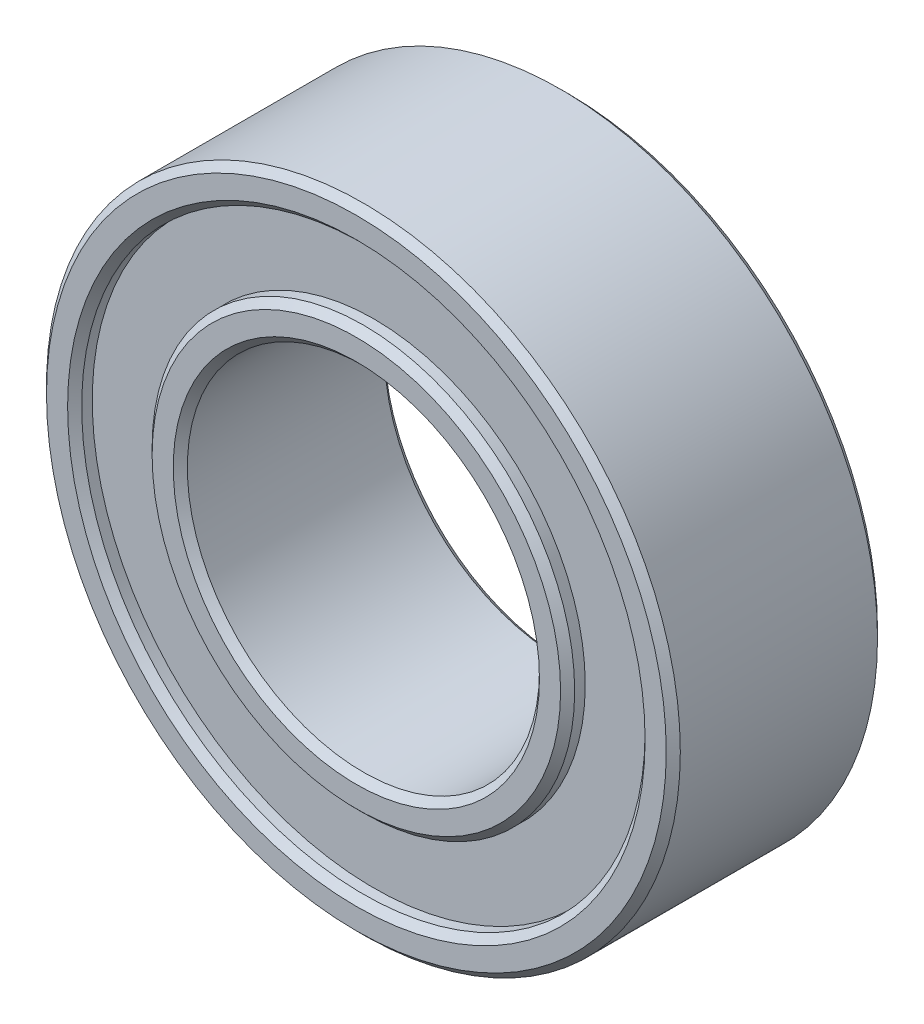
SolidWorks part; units mm, degrees
material "Stainless Steel (ferritic)"
ref_plane "Alzado" through (0, 0, 0) normal (0, 0, 1) x (1, 0, 0)
ref_plane "Planta" through (0, 0, 0) normal (0, 1, 0) x (1, 0, 0)
ref_plane "Vista lateral" through (0, 0, 0) normal (1, 0, 0) x (0, 0, -1)
sketch "Sketch1" plane through (0, 0, 0) normal (0, 0, 1) x (1, 0, 0)
  circle A0 centre (0, 0) radius 4.5
  dimension "D1" = 9
extrude "Boss-Extrude1" add sketch "Sketch1" along normal blind 3
sketch "Sketch2" plane through (0, 0, 3) normal (0, 0, 1) x (1, 0, 0)
  circle A0 centre (0, 0) radius 2.5
  dimension "D1" = 5
extrude "Cut-Extrude1" cut sketch "Sketch2" against normal through all
sketch "Sketch3" plane through (0, 0, 3) normal (0, 0, 1) x (1, 0, 0)
  circle A16 centre (0, 0) radius 4
  circle A17 centre (0, 0) radius 4
  circle A19 centre (0, 0) radius 3
  circle A20 centre (0, 0) radius 3
  dimension "D1" = 0.5
  dimension "D2" = 0.5
extrude "Cut-Extrude3" cut sketch "Sketch3" against normal blind 0.25
sketch "Sketch4" plane through (0, 0, 0) normal (0, 0, -1) x (-1, 0, 0)
  circle A2 centre (0, 0) radius 4
  circle A3 centre (0, 0) radius 4
  circle A5 centre (0, 0) radius 3
  circle A6 centre (0, 0) radius 3
  dimension "D1" = 0.5
  dimension "D2" = 0.5
extrude "Cut-Extrude4" cut sketch "Sketch4" against normal blind 0.25
chamfer "Chamfer3" distance 0.1 angle 45 8 edges at (4.5, 0, 0) (2.5, 0, 0) (-3, 0, 0) (-4, 0, 0) (2.5, 0, 3) (3, 0, 3) (4.5, 0, 3) (4, 0, 3)
